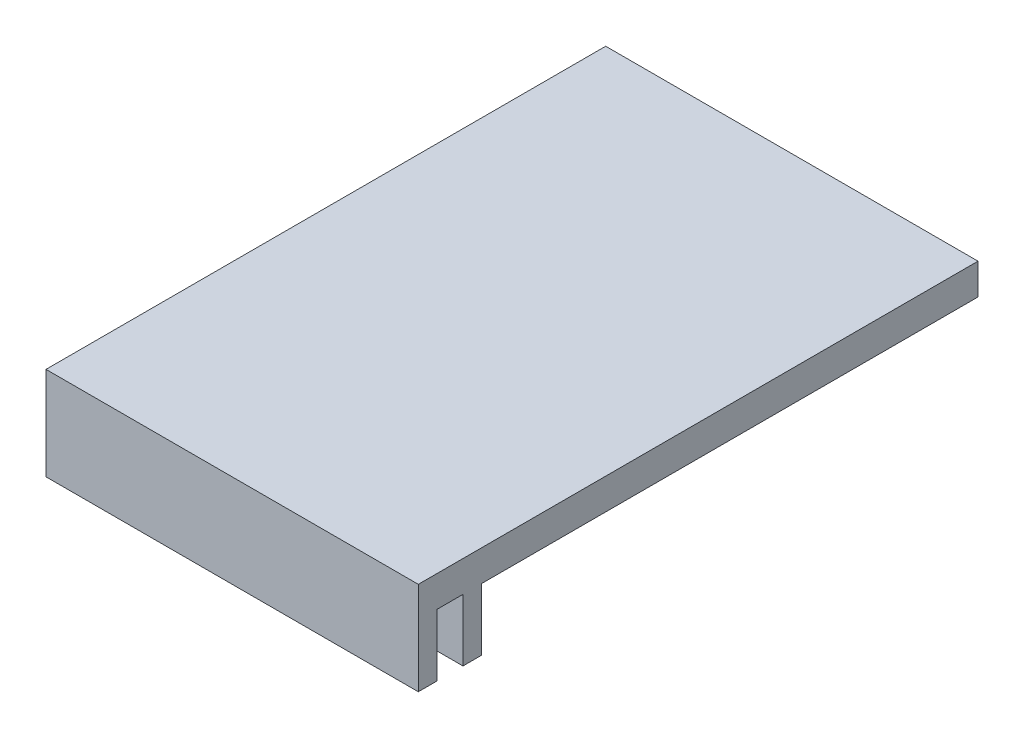
SolidWorks part; units mm, degrees
ref_plane "Front Plane" through (0, 0, 0) normal (0, 0, 1) x (1, 0, 0)
ref_plane "Top Plane" through (0, 0, 0) normal (0, 1, 0) x (1, 0, 0)
ref_plane "Right Plane" through (0, 0, 0) normal (1, 0, 0) x (0, 0, -1)
sketch "Sketch1" plane through (0, 0, 0) normal (0, 1, 0) x (1, 0, 0)
  line L1 (0, 0) -> (20, 0)
  line L2 (0, 0) -> (0, 80)
  line L3 (0, 80) -> (20, 80)
  line L4 (20, 0) -> (20, 80)
  dimension "D1" = 80
  dimension "D2" = 20
extrude "Boss-Extrude1" add sketch "Sketch1" along normal blind 5
sketch "Sketch2" plane through (0, 0, 0) normal (0, -1, 0) x (1, 0, 0)
  line L1 (20, 0) -> (0, 0)
  line L2 (20, 0) -> (20, 10.2)
  line L3 (20, 10.2) -> (0, 10.2)
  line L4 (0, 0) -> (0, 10.2)
  line L5 (0, -80) -> (0, 0) construction
  dimension "D1" = 10.2
  dimension "D2" = 0
extrude "Boss-Extrude2" add sketch "Sketch2" along normal blind 10 and the other way blind 5
sketch "Sketch3" plane through (0, -10, 0) normal (0, -1, 0) x (1, 0, 0)
  line L0 (20, 0) -> (20, 10.2) construction
  line L1 (20, 7.2) -> (0, 7.2)
  line L2 (20, 7.2) -> (20, 3)
  line L3 (20, 3) -> (0, 3)
  line L4 (0, 7.2) -> (0, 3)
  line L5 (0, 10.2) -> (0, 0) construction
  line L6 (0, 0) -> (20, 0) construction
  dimension "D1" = 4.2
  dimension "D2" = 3
extrude "Cut-Extrude1" cut sketch "Sketch3" against normal blind 10
sketch "Sketch5" plane through (0, 0, 0) normal (-1, 0, 0) x (0, 0, 1)
  line L0 (-80, 5) -> (10.2, 5) construction
  line L1 (10.2, -10) -> (7.2, -10)
  line L2 (10.2, -10) -> (10.2, 5)
  line L3 (10.2, 5) -> (7.2, 5)
  line L4 (7.2, -10) -> (7.2, 5)
  line L5 (7.2, 0) -> (7.2, -10) construction
  line M5 (0, -10) -> (3, -10)
  line M6 (3, -10) -> (3, 0)
  line M7 (3, 0) -> (7.2, 0)
  line M8 (7.2, 0) -> (7.2, -10)
  line M9 (7.2, -10) -> (10.2, -10)
  line M10 (10.2, -10) -> (10.2, 5)
  line M11 (10.2, 5) -> (-80, 5)
  line M12 (-80, 5) -> (-80, 0)
  line M13 (-80, 0) -> (0, 0)
  line M14 (0, 0) -> (0, -10)
extrude "Boss-Extrude3" add sketch "Sketch5" along normal blind 40 contours L4 M7 M11 M12 M13 M14 M5 M6 | L4 M8 M9 M10 M11
